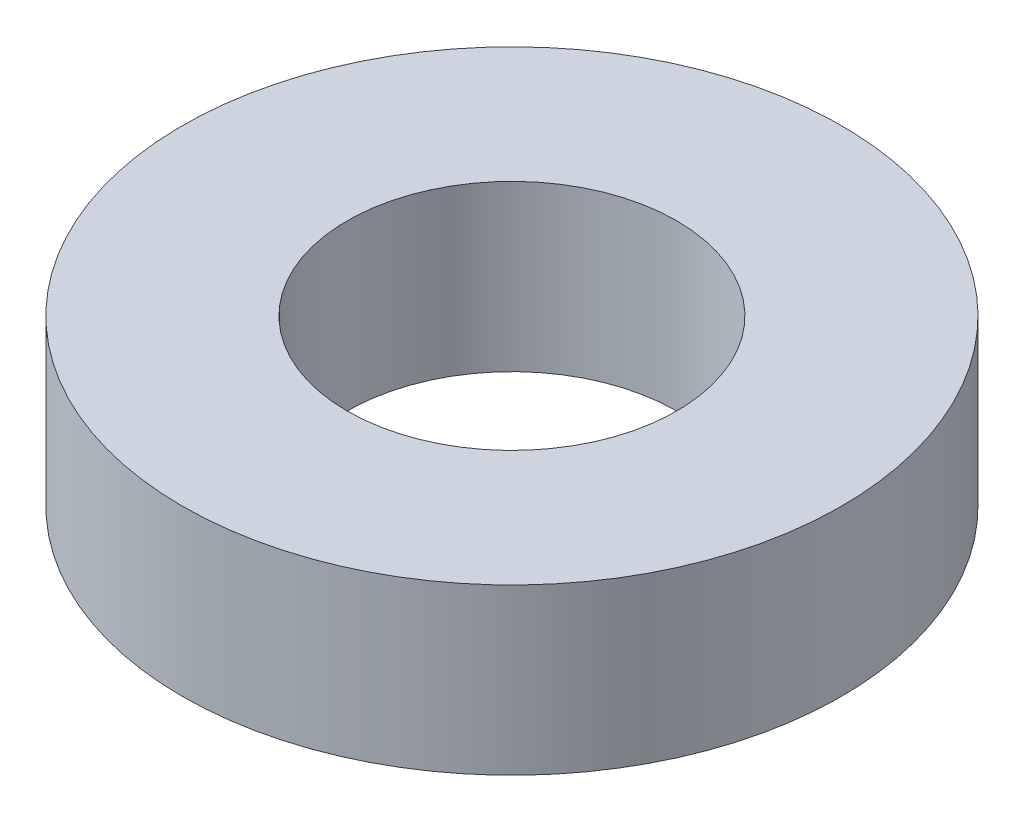
SolidWorks part; units mm, degrees
material "2024-T4"
ref_plane "Front Plane" through (0, 0, 0) normal (0, 0, 1) x (1, 0, 0)
ref_plane "Top Plane" through (0, 0, 0) normal (0, 1, 0) x (1, 0, 0)
ref_plane "Right Plane" through (0, 0, 0) normal (1, 0, 0) x (0, 0, -1)
sketch "Sketch1" plane through (0, 0, 0) normal (0, 1, 0) x (1, 0, 0)
  circle A0 centre (0, 0) radius 200
  circle A1 centre (0, 0) radius 100
extrude "Boss-Extrude1" add sketch "Sketch1" along normal mid plane 100
